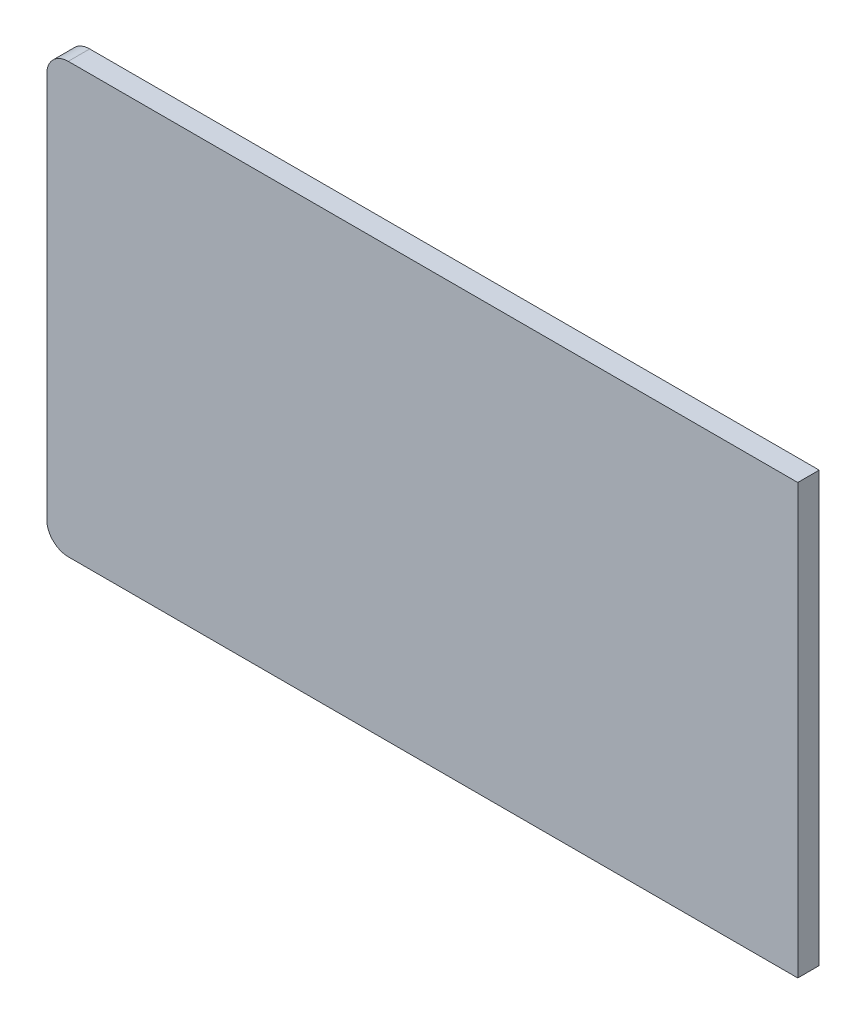
SolidWorks part; units mm, degrees
ref_plane "Plan de face" through (0, 0, 0) normal (0, 0, 1) x (1, 0, 0)
ref_plane "Plan de dessus" through (0, 0, 0) normal (0, 1, 0) x (1, 0, 0)
ref_plane "Plan de droite" through (0, 0, 0) normal (1, 0, 0) x (0, 0, -1)
sketch "Esquisse1" plane through (0, 0, 0) normal (0, 0, 1) x (1, 0, 0)
  line L1 (35, -20) -> (-33, -20)
  line L2 (35, -20) -> (35, 20)
  line L3 (35, 20) -> (-33, 20)
  line L4 (-35, -18) -> (-35, 18)
  line L5 (35, -20) -> (-35, 20) construction
  line L6 (35, 20) -> (-35, -20) construction
  arc A0 (-33, -20) -> (-35, -18) centre (-33, -18) cw
  arc A1 (-33, 20) -> (-35, 18) centre (-33, 18) ccw
  point P0 (0, 0)
  dimension "D3" = 2
  dimension "D1" = 70
  dimension "D2" = 40
extrude "Boss.-Extru.1" add sketch "Esquisse1" along normal blind 2
